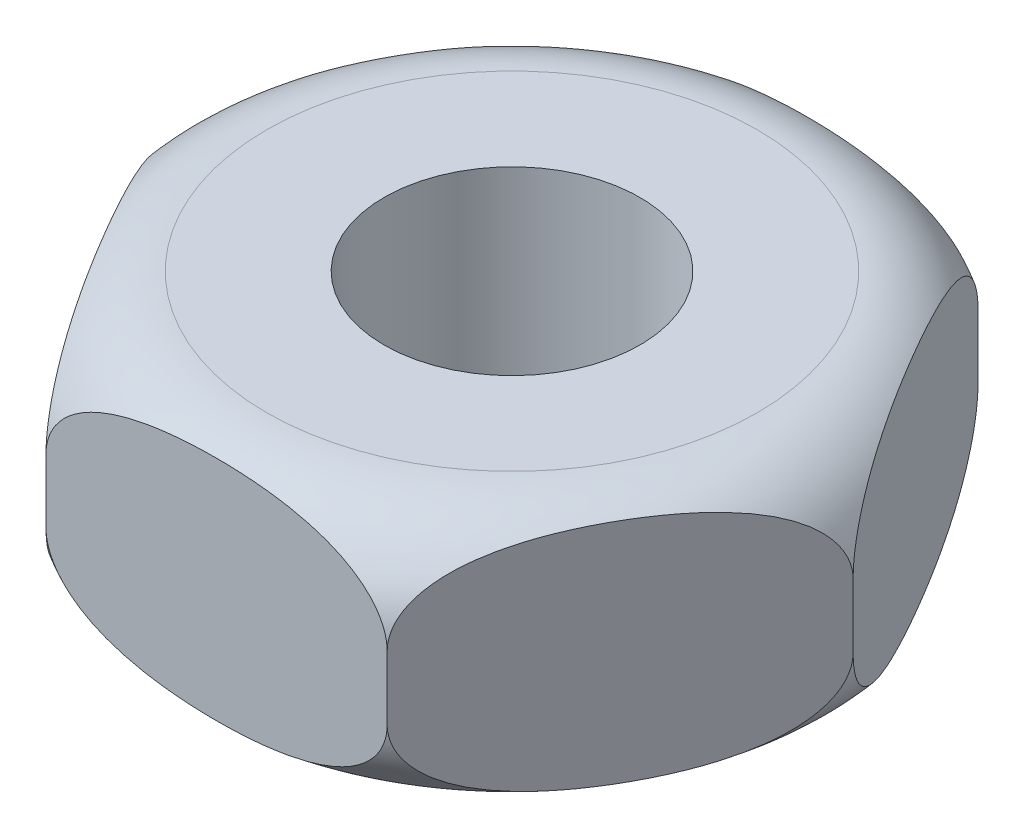
SolidWorks part; units mm, degrees
ref_plane "Front Plane" through (0, 0, 0) normal (0, 0, 1) x (1, 0, 0)
ref_plane "Top Plane" through (0, 0, 0) normal (0, 1, 0) x (1, 0, 0)
ref_plane "Right Plane" through (0, 0, 0) normal (1, 0, 0) x (0, 0, -1)
sketch "Sketch1" plane through (0, 0, 0) normal (0, 1, 0) x (1, 0, 0)
  line L1 (16, 0) -> (8, 13.8564)
  line L2 (8, 13.8564) -> (-8, 13.8564)
  line L3 (-8, 13.8564) -> (-16, 0)
  line L4 (-16, 0) -> (-8, -13.8564)
  line L5 (-8, -13.8564) -> (8, -13.8564)
  line L6 (8, -13.8564) -> (16, 0)
  circle A0 centre (0, 0) radius 13.8564 construction
  circle A1 centre (0, 0) radius 6
  dimension "D2" = 12
  dimension "D1" = 32
extrude "Boss-Extrude1" add sketch "Sketch1" along normal mid plane 12
sketch "Sketch2" plane through (0, 0, 0) normal (0, 0, 1) x (1, 0, 0)
  line L1 (0, 9.9437) -> (0, -10.9877) construction
  line L6 (11.5, 6) -> (16, 6)
  line L7 (16, 6) -> (16, 1.5)
  line L8 (11.5, -6) -> (16, -6)
  line L9 (16, -6) -> (16, -1.5)
  arc A0 (16, 1.5) -> (11.5, 6) centre (11.5, 1.5) ccw
  arc A1 (11.5, -6) -> (16, -1.5) centre (11.5, -1.5) ccw
  dimension "D1" = 4.5
  dimension "D2" = 4.5
revolve "Cut-Revolve2" cut sketch "Sketch2" angle 360 about L1
